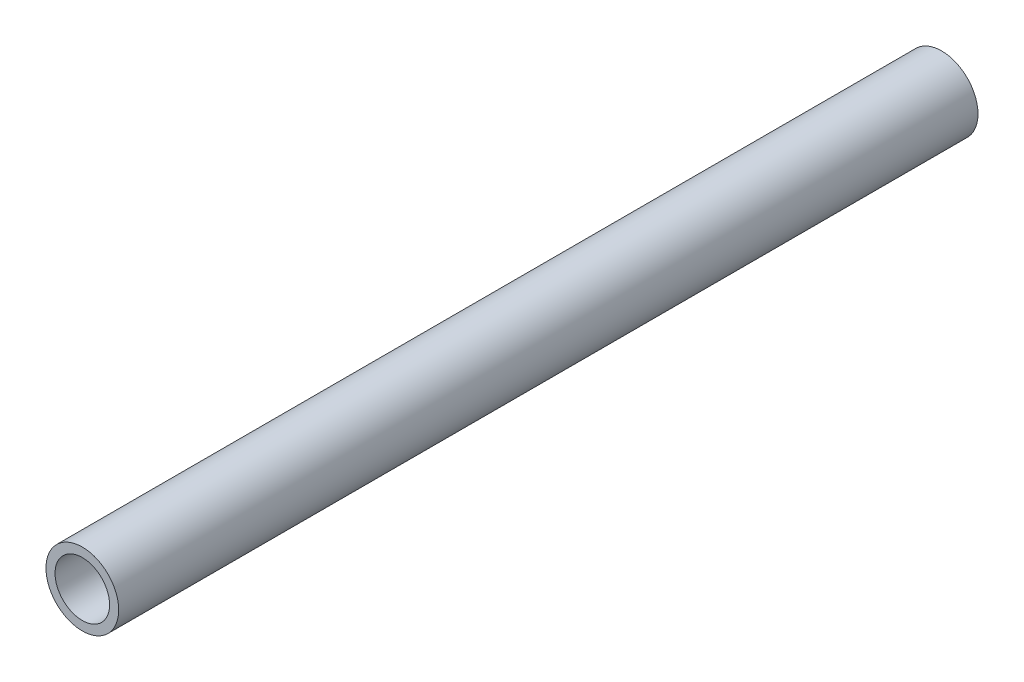
SolidWorks part; units mm, degrees
material "Nylon 6/10"
ref_plane "Front Plane" through (0, 0, 0) normal (0, 0, 1) x (1, 0, 0)
ref_plane "Top Plane" through (0, 0, 0) normal (0, 1, 0) x (1, 0, 0)
ref_plane "Right Plane" through (0, 0, 0) normal (1, 0, 0) x (0, 0, -1)
sketch "Sketch1" plane through (0, 0, 0) normal (0, 0, 1) x (1, 0, 0)
  circle A0 centre (0, 0) radius 6.35
  circle A1 centre (0, 0) radius 4.7625
  dimension "D1" = 12.7
  dimension "D2" = 9.525
extrude "Boss-Extrude1" add sketch "Sketch1" along normal blind 150
